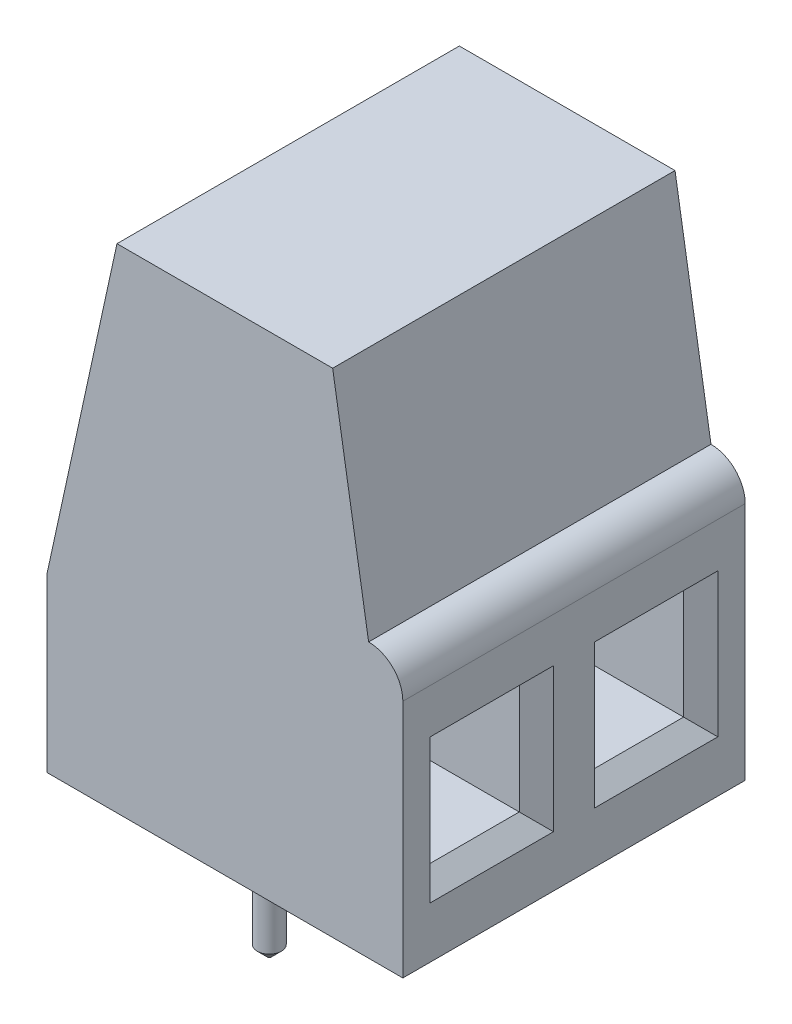
SolidWorks part; units mm, degrees
ref_plane "Plano frontal" through (0, 0, 0) normal (0, 0, 1) x (1, 0, 0)
ref_plane "Plano superior" through (0, 0, 0) normal (0, 1, 0) x (1, 0, 0)
ref_plane "Plano direito" through (0, 0, 0) normal (1, 0, 0) x (0, 0, -1)
sketch "Esboço2" plane through (0, 0, 0) normal (0, 0, 1) x (1, 0, 0)
  line L0 (0, 0) -> (10.4, 0)
  line L2 (0, 0) -> (0, 5)
  line L3 (10.4, 0) -> (10.4, 7)
  line L4 (5.2, 14.4) -> (8.35, 14.4)
  line L5 (2.05, 14.4) -> (0, 5)
  line L7 (5.2, 14.4) -> (2.05, 14.4)
  line L8 (8.35, 14.4) -> (9.4, 8)
  arc A0 (10.4, 7) -> (9.4, 8) centre (9.4, 7) ccw
  dimension "D1" = 10.4
  dimension "D2" = 5
  dimension "D3" = 7
  dimension "D5" = 1
extrude "Ressalto-extrusão2" add sketch "Esboço2" against normal blind 10
sketch "Esboço4" plane through (10.4, 0, 0) normal (1, 0, 0) x (0, 0, -1)
  line L0 (10, 0) -> (10, 7) construction
  line L2 (0, 0) -> (0, 7) construction
  line L5 (1.3, 2) -> (3.9, 2)
  line L6 (1.3, 2) -> (1.3, 5.2)
  line L7 (1.3, 5.2) -> (3.9, 5.2)
  line L8 (3.9, 2) -> (3.9, 5.2)
  line L12 (8.7, 2) -> (6.1, 2)
  line L13 (8.7, 2) -> (8.7, 5.2)
  line L14 (8.7, 5.2) -> (6.1, 5.2)
  line L15 (6.1, 2) -> (6.1, 5.2)
  dimension "D1" = 1.3
  dimension "D2" = 1.3
  dimension "D3" = 3.2
  dimension "D4" = 2.6
  dimension "D7" = 2.6
extrude "Corte-extrusão1" cut sketch "Esboço4" against normal blind 5
chamfer "Chanfro2" distance 0.5 angle 45 4 edges at (10.4, 2, -2.6) (10.4, 3.6, -3.9) (10.4, 5.2, -2.6) (10.4, 3.6, -1.3)
chamfer "Chanfro3" distance 0.5 angle 45 4 edges at (10.4, 3.6, -6.1) (10.4, 2, -7.4) (10.4, 3.6, -8.7) (10.4, 5.2, -7.4)
sketch "Esboço10" plane through (0, 0, 0) normal (0, -1, 0) x (1, 0, 0)
  line L0 (0, -10) -> (0, 0) construction
  line L1 (0, 0) -> (10.4, 0) construction
  line L2 (0, -10) -> (10.4, -10) construction
  circle A0 centre (4.3, -2.2) radius 0.35
  circle A1 centre (4.3, -7.8) radius 0.35
  dimension "D1" = 4.3
  dimension "D2" = 4.3
  dimension "D3" = 2.2
  dimension "D4" = 2.2
extrude "Ressalto-extrusão5" add sketch "Esboço10" along normal blind 3.6
chamfer "Chanfro4" distance 0.3 angle 45 2 edges at (4.3, -3.6, -8.15) (4.3, -3.6, -2.55)
